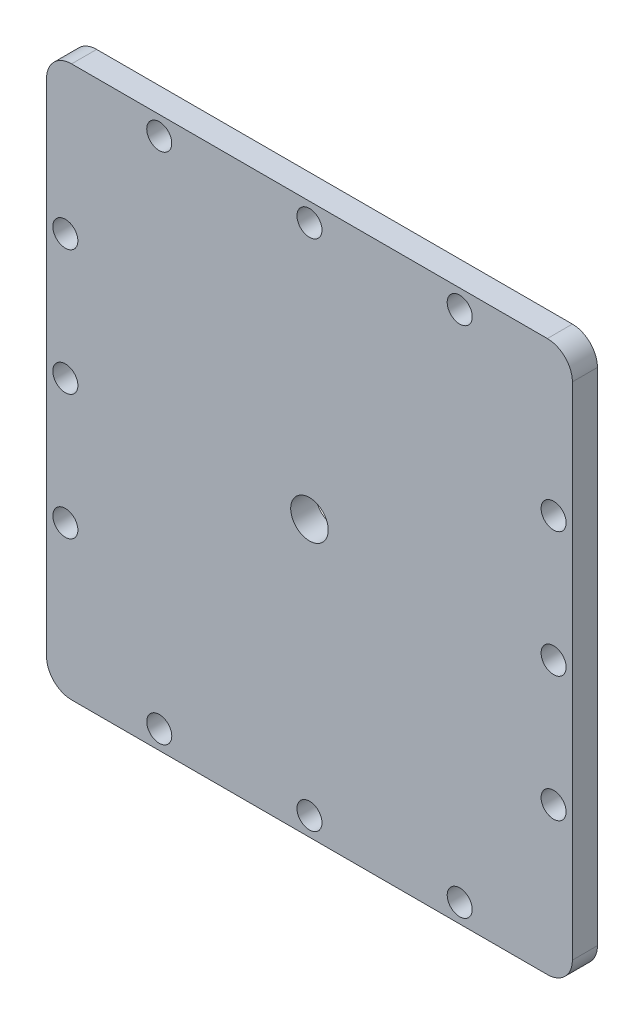
SolidWorks part; units mm, degrees
ref_plane "前视基准面" through (0, 0, 0) normal (0, 0, 1) x (1, 0, 0)
ref_plane "上视基准面" through (0, 0, 0) normal (0, 1, 0) x (1, 0, 0)
ref_plane "右视基准面" through (0, 0, 0) normal (1, 0, 0) x (0, 0, -1)
sketch "草图1" plane through (0, 0, 0) normal (0, 0, 1) x (1, 0, 0)
  line L0 (0, 0) -> (0, 102.5) construction
  line L5 (-95, -110) -> (95, -110)
  line L6 (-105, -100) -> (-105, 100)
  line L11 (-95, 110) -> (95, 110)
  line L12 (105, -100) -> (105, 100)
  line L13 (-105, -110) -> (105, 110) construction
  line L14 (-105, 110) -> (105, -110) construction
  line L15 (-97.5, -102.5) -> (97.5, -102.5) construction
  line L16 (-97.5, -102.5) -> (-97.5, 102.5) construction
  line L17 (-97.5, 102.5) -> (97.5, 102.5) construction
  line L18 (97.5, -102.5) -> (97.5, 102.5) construction
  line L19 (-97.5, -102.5) -> (97.5, 102.5) construction
  line L20 (-97.5, 102.5) -> (97.5, -102.5) construction
  line L21 (0, 0) -> (97.5, 0) construction
  arc A5 (95, 110) -> (105, 100) centre (95, 100) cw
  arc A6 (95, -110) -> (105, -100) centre (95, -100) ccw
  arc A7 (-95, -110) -> (-105, -100) centre (-95, -100) cw
  arc A8 (-105, 100) -> (-95, 110) centre (-95, 100) cw
  circle A9 centre (97.5, 0) radius 5
  circle A10 centre (0, 102.5) radius 5
  circle A11 centre (60, 102.5) radius 5
  circle A12 centre (97.5, 50) radius 5
  circle A13 centre (97.5, -50) radius 5
  circle A14 centre (60, -102.5) radius 5
  circle A15 centre (0, -102.5) radius 5
  circle A16 centre (-60, 102.5) radius 5
  circle A17 centre (-60, -102.5) radius 5
  circle A18 centre (-97.5, -50) radius 5
  circle A19 centre (-97.5, 0) radius 5
  circle A20 centre (-97.5, 50) radius 5
  point P0 (0, 0)
  point P18 (0, 0)
  dimension "D3" = 10
  dimension "D6" = 10
  dimension "D7" = 10
  dimension "D8" = 10
  dimension "D10" = 10
  dimension "D1" = 220
  dimension "D2" = 210
  dimension "D4" = 205
  dimension "D5" = 195
  dimension "D9" = 60
  dimension "D11" = 50
extrude "凸台-拉伸1" add sketch "草图1" along normal blind 10
sketch "草图2" plane through (0, 0, 10) normal (0, 0, 1) x (1, 0, 0)
  circle A0 centre (0, 0) radius 7.5
  dimension "D1" = 15
extrude "切除-拉伸1" cut sketch "草图2" against normal through all
